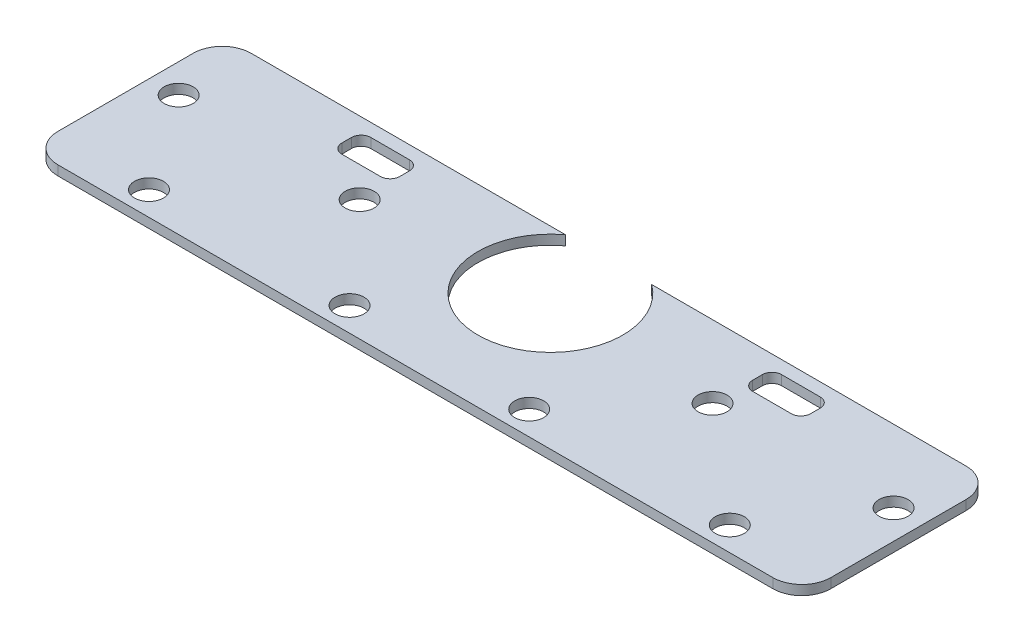
SolidWorks part; units mm, degrees
ref_plane "Front Plane" through (0, 0, 0) normal (0, 0, 1) x (1, 0, 0)
ref_plane "Top Plane" through (0, 0, 0) normal (0, 1, 0) x (1, 0, 0)
ref_plane "Right Plane" through (0, 0, 0) normal (1, 0, 0) x (0, 0, -1)
sketch "Sketch1" plane through (0, 0, 0) normal (0, 1, 0) x (1, 0, 0)
  line L0 (-415.0151, 97.0124) -> (383.6515, 97.0124) construction
  line L1 (370, -100) -> (-370, -100)
  line L2 (400, -70) -> (400, 70)
  line L3 (370, 100) -> (-370, 100)
  line L4 (-400, -70) -> (-400, 70)
  line L5 (400, -100) -> (-400, 100) construction
  line L6 (400, 100) -> (-400, -100) construction
  line L7 (0, -100) -> (0, 100) construction
  line L8 (-232.6235, 86.4681) -> (-192.6235, 86.4681)
  line L9 (-242.6235, 76.4681) -> (-242.6235, 66.4681)
  line L10 (-232.6235, 56.4681) -> (-192.6235, 56.4681)
  line L11 (-182.6235, 76.4681) -> (-182.6235, 66.4681)
  line L12 (-242.6235, 86.4681) -> (-182.6235, 56.4681) construction
  line L13 (-242.6235, 56.4681) -> (-182.6235, 86.4681) construction
  line L14 (232.6235, 56.4681) -> (192.6235, 56.4681)
  line L15 (182.6235, 76.4681) -> (182.6235, 66.4681)
  line L16 (232.6235, 86.4681) -> (192.6235, 86.4681)
  line L17 (242.6235, 76.4681) -> (242.6235, 66.4681)
  arc A0 (400, 70) -> (370, 100) centre (370, 70) ccw
  arc A1 (400, -70) -> (370, -100) centre (370, -70) cw
  arc A2 (-370, -100) -> (-400, -70) centre (-370, -70) cw
  arc A3 (-400, 70) -> (-370, 100) centre (-370, 70) cw
  arc A4 (-192.6235, 86.4681) -> (-182.6235, 76.4681) centre (-192.6235, 76.4681) cw
  arc A5 (-182.6235, 66.4681) -> (-192.6235, 56.4681) centre (-192.6235, 66.4681) cw
  arc A6 (-232.6235, 56.4681) -> (-242.6235, 66.4681) centre (-232.6235, 66.4681) cw
  arc A7 (-232.6235, 86.4681) -> (-242.6235, 76.4681) centre (-232.6235, 76.4681) ccw
  circle A8 centre (0, 39.7168) radius 75
  circle A10 centre (-370, 24.9492) radius 15
  circle A12 centre (-92.9796, -75.1545) radius 15
  circle A13 centre (-182.6235, 24.9492) radius 15
  circle A16 centre (-300.6182, -75.1545) radius 15
  circle A17 centre (92.9796, -75.1545) radius 15
  circle A18 centre (182.6235, 24.9492) radius 15
  circle A19 centre (300.6182, -75.1545) radius 15
  circle A20 centre (370, 24.9492) radius 15
  arc A21 (182.6235, 66.4681) -> (192.6235, 56.4681) centre (192.6235, 66.4681) ccw
  arc A22 (192.6235, 86.4681) -> (182.6235, 76.4681) centre (192.6235, 76.4681) ccw
  arc A23 (232.6235, 56.4681) -> (242.6235, 66.4681) centre (232.6235, 66.4681) ccw
  arc A24 (232.6235, 86.4681) -> (242.6235, 76.4681) centre (232.6235, 76.4681) cw
  point P0 (0, 0)
  point P20 (-212.6235, 71.4681)
  dimension "D3" = 30
  dimension "D4" = 10
  dimension "D5" = 150
  dimension "D8" = 10
  dimension "D9" = 30
  dimension "D1" = 800
  dimension "D2" = 200
  dimension "D6" = 60
  dimension "D7" = 30
extrude "Boss-Extrude1" add sketch "Sketch1" along normal blind 10 contours A8 L3 A3 L4 A2 L1 A1 L2 A0 A19 A17 A16 A13 A12 A10 A7 L8 A4 L11 A5 L10 A6 L9 A18 A20 L16 A24 L17 A23 L14 A21 L15 A22
